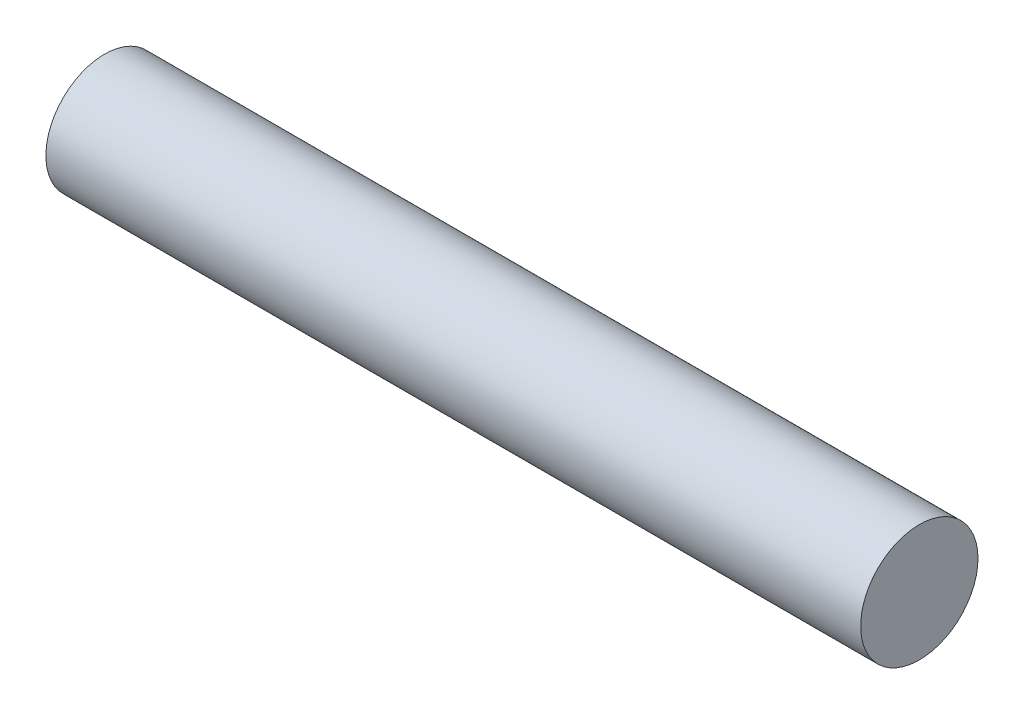
SolidWorks part; units mm, degrees
ref_plane "前视基准面" through (0, 0, 0) normal (0, 0, 1) x (1, 0, 0)
ref_plane "上视基准面" through (0, 0, 0) normal (0, 1, 0) x (1, 0, 0)
ref_plane "右视基准面" through (0, 0, 0) normal (1, 0, 0) x (0, 0, -1)
other "Configuration Table"
sketch "草图4" plane through (0, 0, 0) normal (1, 0, 0) x (0, 0, -1)
  circle A0 centre (0, 0) radius 2.5
  dimension "D1" = 5
sketch "草图5" plane through (0, 0, 0) normal (1, 0, 0) x (0, 0, -1)
  circle A0 centre (0, 0) radius 1.8
  circle A2 centre (0, 0) radius 2.5 construction
  dimension "D1" = 0.7
extrude "凸台-拉伸1" add sketch "草图5" along normal blind 25
sketch "草图6" plane through (0, 0, 0) normal (-1, 0, 0) x (0, 0, 1)
  circle A0 centre (0, 0) radius 1.8
  circle A1 centre (0, 0) radius 1.8 construction
sketch "草图7" plane through (25, 0, 0) normal (1, 0, 0) x (0, 0, -1)
  circle A0 centre (0, 0) radius 1.8
  circle A1 centre (0, 0) radius 1.8 construction
